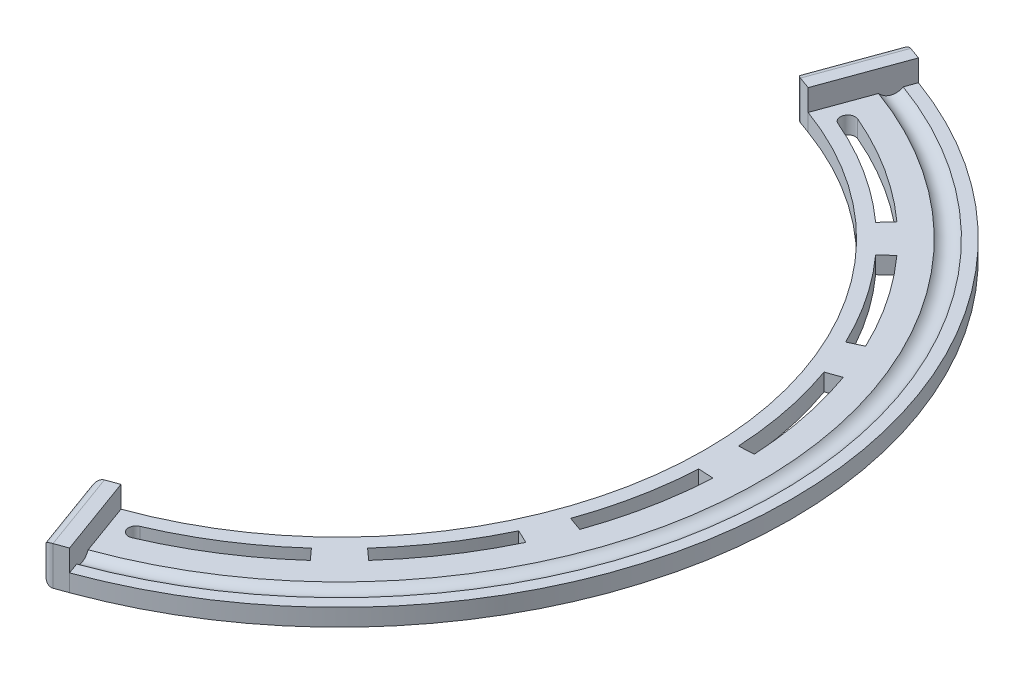
SolidWorks part; units mm, degrees
ref_plane "前视基准面" through (0, 0, 0) normal (0, 0, 1) x (1, 0, 0)
ref_plane "上视基准面" through (0, 0, 0) normal (0, 1, 0) x (1, 0, 0)
ref_plane "右视基准面" through (0, 0, 0) normal (1, 0, 0) x (0, 0, -1)
sketch "草图1" plane through (0, 0, 0) normal (0, 1, 0) x (1, 0, 0)
  line L0 (0, 0) -> (98.6677, -35.9121)
  line L1 (0, 0) -> (98.6677, 35.9121)
  line L2 (0, 0) -> (105, 0) construction
  line L3 (0, 0) -> (52.5, -90.9327)
  line L4 (0, 0) -> (52.5, 90.9327)
  circle A0 centre (0, 0) radius 100
  circle A1 centre (0, 0) radius 105
  circle A2 centre (0, 0) radius 95
  dimension "D1" = 200
  dimension "D2" = 210
  dimension "D3" = 190
  dimension "D4" = 20
  dimension "D5" = 20
  dimension "D6" = 60
  dimension "D7" = 60
sketch "草图2" plane through (0, 0, 0) normal (0, 0, 1) x (1, 0, 0)
  line L0 (0, 0) -> (100, 0) construction
  line L1 (0, 0) -> (98.6677, 0) construction
  line L2 (100, 0) -> (100, -8) construction
  line L3 (95, 2) -> (105, 2)
  line L4 (95, 2) -> (95, -2)
  line L5 (95, -2) -> (105, -2)
  line L6 (105, 2) -> (105, -2)
  line L7 (95, 2) -> (105, -2) construction
  line L8 (95, -2) -> (105, 2) construction
  line L9 (95, -6) -> (105, -6)
  line L10 (95, -6) -> (95, -10)
  line L11 (95, -10) -> (105, -10)
  line L12 (105, -6) -> (105, -10)
  line L13 (95, -6) -> (105, -10) construction
  line L14 (95, -10) -> (105, -6) construction
  line L15 (95, -3) -> (95, -2)
  line L16 (96.5, -3) -> (103.5, -3)
  line L17 (96.5, -3) -> (96.5, -5)
  line L18 (96.5, -5) -> (103.5, -5)
  line L19 (103.5, -3) -> (103.5, -5)
  line L20 (96.5, -3) -> (103.5, -5) construction
  line L21 (96.5, -5) -> (103.5, -3) construction
  line L22 (95, -3) -> (105, -3)
  line L23 (95, -3) -> (95, -5)
  line L24 (95, -5) -> (105, -5)
  line L25 (105, -3) -> (105, -5)
  line L26 (95, -3) -> (105, -5) construction
  line L27 (95, -5) -> (105, -3) construction
  line L28 (95, -2) -> (96.5, -2)
  line L29 (96.5, -2) -> (96.5, -3)
  line L30 (95, -6) -> (85, -6)
  line L31 (85, -6) -> (85, -10)
  line L32 (85, -10) -> (95, -10)
  line L36 (103.5, -3) -> (103.5, -2)
  line L37 (103.5, -2) -> (105, -2)
  line L38 (105, -2) -> (105, -3)
  line L39 (95, 2) -> (95, 4)
  line L40 (95, 4) -> (85, 4)
  line L41 (85, 4) -> (85, 7)
  line L42 (85, 7) -> (105, 7)
  line L43 (105, 7) -> (105, 2)
  line L44 (0, 24.3669) -> (0, -24.3669) construction
  circle A0 centre (100, -4) radius 3
  point P11 (100, -8)
  point P40 (0, 0)
  dimension "D7" = 6
  dimension "D1" = 100
  dimension "D2" = 10
  dimension "D3" = 4
  dimension "D4" = 4
  dimension "D5" = 4
  dimension "D6" = 10
  dimension "D8" = 7
  dimension "D9" = 10
  dimension "D10" = 2
  dimension "D11" = 2
  dimension "D12" = 1
  dimension "D13" = 10
  dimension "D14" = 1
  dimension "D16" = 5
  dimension "D17" = 3
  dimension "D18" = 20
revolve "旋转1" add sketch "草图2" angle 140 mid plane about L44
sketch "草图3" plane through (0, 0, 0) normal (-0.9397, 0, 0.342) x (0.342, 0, 0.9397)
  line L0 (85, -6) -> (85, -1)
  line L1 (85, -1) -> (105, -1)
  line L2 (105, -1) -> (105, -6)
  line L5 (97.7639, -6) -> (85, -6)
  line L6 (85, -6) -> (85, -10)
  line L7 (85, -10) -> (105, -10)
  line L8 (105, -10) -> (105, -6)
  line L9 (105, -6) -> (102.2361, -6)
  line L10 (97.7639, -6) -> (85, -6)
  line L12 (85, -10) -> (105, -10)
  line L13 (105, -10) -> (105, -6)
  line L14 (105, -6) -> (102.2361, -6)
  line L18 (85, -6) -> (85, -10)
  arc A1 (97.7639, -6) -> (102.2361, -6) centre (100, -4) ccw
  arc A2 (97.7639, -6) -> (102.2361, -6) centre (100, -4) ccw
  dimension "D2" = 5
  dimension "D1" = 0
extrude "凸台-拉伸1" add sketch "草图3" along normal blind 5
sketch "草图4" plane through (0, 0, 0) normal (-0.9397, 0, -0.342) x (-0.342, 0, 0.9397)
  line L0 (-105, -6) -> (-105, -1)
  line L1 (-105, -1) -> (-85, -1)
  line L2 (-85, -1) -> (-85, -6)
  line L5 (-102.2361, -6) -> (-105, -6)
  line L6 (-105, -6) -> (-105, -10)
  line L7 (-105, -10) -> (-85, -10)
  line L8 (-85, -10) -> (-85, -6)
  line L9 (-85, -6) -> (-97.7639, -6)
  line L10 (-102.2361, -6) -> (-105, -6)
  line L11 (-105, -6) -> (-105, -10)
  line L12 (-105, -10) -> (-85, -10)
  line L14 (-85, -6) -> (-97.7639, -6)
  line L18 (-85, -10) -> (-85, -6)
  arc A1 (-102.2361, -6) -> (-97.7639, -6) centre (-100, -4) ccw
  arc A2 (-102.2361, -6) -> (-97.7639, -6) centre (-100, -4) ccw
  dimension "D2" = 5
  dimension "D1" = 0
extrude "凸台-拉伸2" add sketch "草图4" along normal blind 5
sketch "草图5" plane through (0, -6, 0) normal (0, 1, 0) x (1, 0, 0)
  line L0 (29.0717, 79.8739) -> (33.4372, 91.868) construction
  line L1 (29.0717, -79.8739) -> (35.9121, -98.6677) construction
  circle A0 centre (35.4327, 82.7316) radius 1.75
  circle A1 centre (35.4327, -82.7316) radius 1.75
  circle A2 centre (0, 0) radius 90
  circle A3 centre (0, 0) radius 88.25
  circle A4 centre (0, 0) radius 91.75
  dimension "D1" = 3.5
  dimension "D2" = 3.5
  dimension "D3" = 180
  dimension "D4" = 5
  dimension "5" = 5
extrude "切除-拉伸1" cut sketch "草图5" against normal blind 5 contours A2 A0 | A0 A2 | A1 A4 A0 A2 | A3 A1 A2 A0 | A1 A2 | A2 A1
fillet "圆角1" radius 2 8 edges at (27.7935, -1, -90.9809) (24.3732, -5.5, -81.584) (27.7935, -10, -90.9809) (31.2137, -5.5, -100.3778) (27.7935, -1, 90.9809) (31.2137, -5.5, 100.3778) (27.7935, -10, 90.9809) (24.3732, -5.5, 81.584)
sketch "草图6" plane through (0, -10, 0) normal (0, -1, 0) x (1, 0, 0)
  line L0 (0, 0) -> (91.6243, 4.8018)
  line L1 (0, 0) -> (91.6243, -4.8018)
  line L2 (0, 0) -> (0, 128.4907) construction
  line L3 (0, 0) -> (91.75, 0) construction
  line L4 (0, 0) -> (82.8122, -39.4994)
  line L5 (0, 0) -> (86.4874, -30.6268)
  line L6 (0, 0) -> (84.7659, -35.1112) construction
  line L7 (0, 0) -> (61.3927, -68.1835)
  line L8 (0, 0) -> (68.1835, -61.3927)
  line L9 (0, 0) -> (64.877, -64.877) construction
  line L10 (0, 0) -> (86.4874, 30.6268)
  line L11 (0, 0) -> (84.7659, 35.1112) construction
  line L12 (0, 0) -> (82.8122, 39.4994)
  line L13 (0, 0) -> (68.1835, 61.3927)
  line L14 (0, 0) -> (64.877, 64.877) construction
  line L15 (0, 0) -> (61.3927, 68.1835)
  circle A0 centre (0, 0) radius 85
  circle A1 centre (0, 0) radius 88.25
  circle A2 centre (0, 0) radius 91.75
  point P18 (0, 0)
  point P26 (0, 0)
  arc M7 (36.1217, 84.3403) -> (36.1217, -84.3403) centre (0, 0) cw
  arc M9 (34.7438, -81.123) -> (34.7438, 81.123) centre (0, 0) ccw
  dimension "D1" = 170
  dimension "D2" = 176.5
  dimension "D3" = 183.5
  dimension "D4" = 6
  dimension "D5" = 3
  dimension "D8" = 22.5
  dimension "D9" = 22.5
  dimension "D6" = 3
  dimension "D7" = 3
extrude "凸台-拉伸3" add sketch "草图6" against normal blind 4 contours L15 L13 M9 M7 | L12 L10 M9 M7 | L1 L0 M9 M7 | L5 L4 M9 M7 | L8 L7 M9 M7
